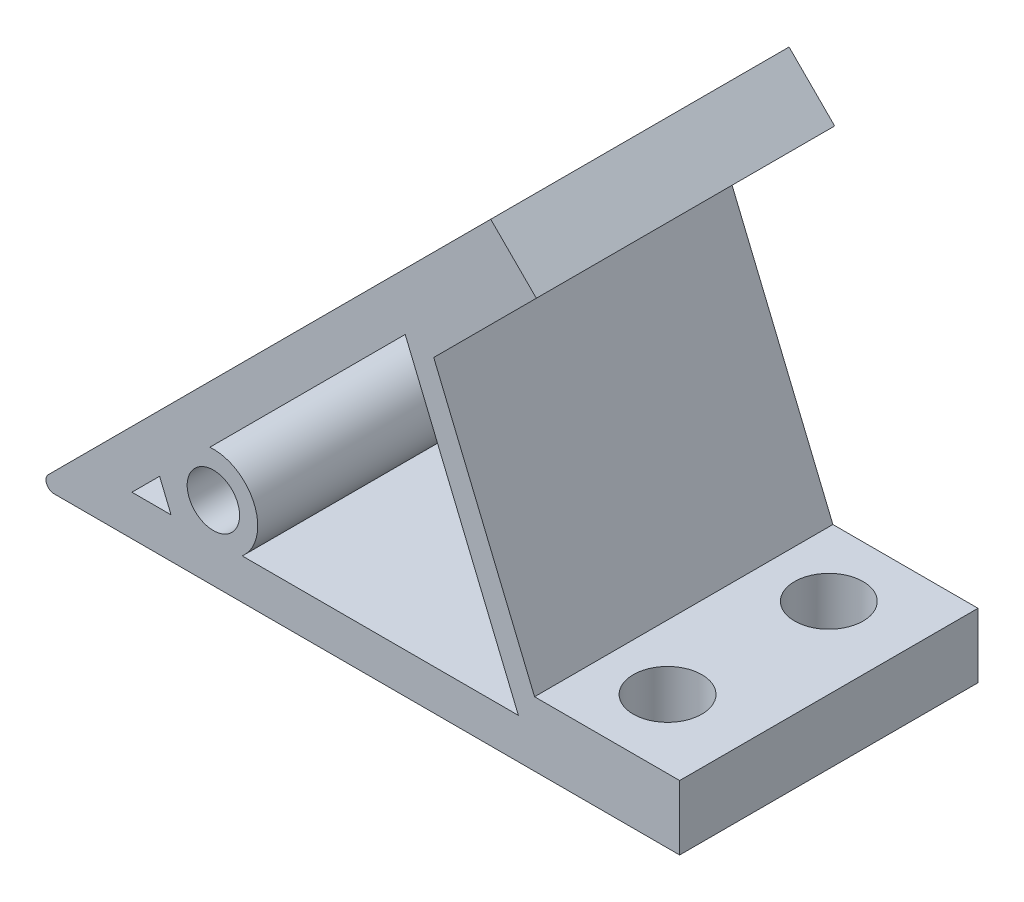
SolidWorks part; units mm, degrees
ref_plane "前视基准面" through (0, 0, 0) normal (0, 0, 1) x (1, 0, 0)
ref_plane "上视基准面" through (0, 0, 0) normal (0, 1, 0) x (1, 0, 0)
ref_plane "右视基准面" through (0, 0, 0) normal (1, 0, 0) x (0, 0, -1)
sketch "草图1" plane through (0, 0, 0) normal (0, 0, 1) x (1, 0, 0)
  line B0 (-77.5858, 0) -> (0, 0)
  line B1 (-67.9289, 5) -> (-63.0745, 5)
  line B2 (-54.2575, 5) -> (-20, 5)
  line B3 (-17.9955, 8) -> (0, 8)
  line B4 (-78.2929, 1.7071) -> (-23.4315, 56.5685)
  line B5 (-67.9289, 5) -> (-64.4963, 8.4326)
  line B6 (-58.2617, 14.6672) -> (-34.0381, 38.8909)
  line B7 (-30.4993, 38.187) -> (-17.7746, 50.9117)
  line B8 (0, 0) -> (0, 8)
  line B9 (-17.7746, 50.9117) -> (-23.4315, 56.5685)
  line B10 (-20, 5) -> (-34.0381, 38.8909)
  line B11 (-17.9955, 8) -> (-30.4993, 38.187)
  line B12 (-63.0745, 5) -> (-64.4963, 8.4326)
  arc B13 (-78.2929, 1.7071) -> (-77.5858, 0) centre (-77.5858, 1) ccw
  circle B14 centre (-57.8269, 9.1844) radius 3.25
  arc B15 (-54.2575, 5) -> (-58.2617, 14.6672) centre (-57.8269, 9.1844) ccw
sketch_block_instance "A$C18907C9D-1"
sketch_block "A$C18907C9D"
extrude "凸台-拉伸1" add sketch "草图1" along normal mid plane 37
sketch "草图3" plane through (0, 8, 0) normal (0, 1, 0) x (1, 0, 0)
  line L0 (0, -18.5) -> (0, 18.5) construction
  line L1 (0, -18.5) -> (-17.9955, -18.5) construction
  line L2 (0, 0) -> (-16.9231, 0) construction
  circle A0 centre (-10, -10) radius 4.25
  circle A1 centre (-10, 10) radius 4.25
  dimension "D1" = 10
  dimension "D2" = 8.5
extrude "切除-拉伸1" cut sketch "草图3" against normal blind 17
sketch "草图4" plane through (-12.5317, -5.1908, 0) normal (0.9239, 0.3827, 0) x (0, 0, -1)
  line L0 (-18.5, 30.6147) -> (18.5, 30.6147) construction
  line L1 (-18.5, 14.2776) -> (-18.5, 46.9517) construction
  line L2 (18.5, 14.2776) -> (18.5, 46.9517) construction
ref_plane "基准面2" through (-11.7157, 28.2843, 0) normal (-0.3827, 0.9239, 0) x (0.9239, 0.3827, 0)
mirror "镜向1" about plane through (-11.7157, 28.2843, 0) normal (-0.3827, 0.9239, 0) of "切除-拉伸1"
